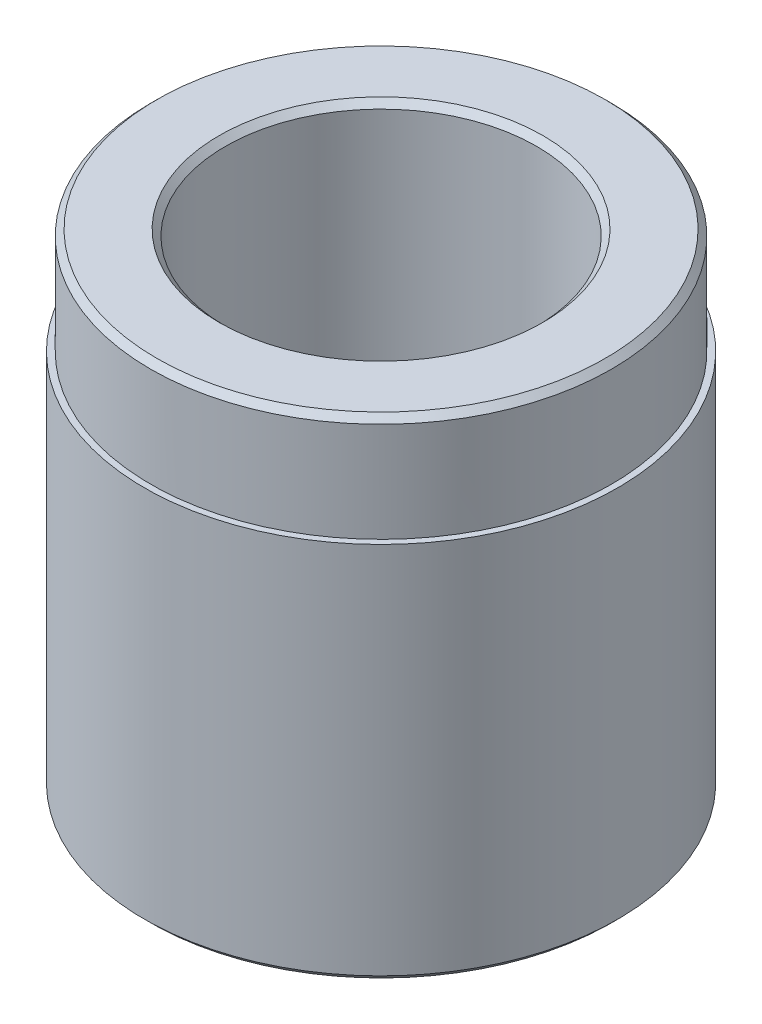
SolidWorks part; units mm, degrees
material "20"
ref_plane "前视基准面" through (0, 0, 0) normal (0, 0, 1) x (1, 0, 0)
ref_plane "上视基准面" through (0, 0, 0) normal (0, 1, 0) x (1, 0, 0)
ref_plane "右视基准面" through (0, 0, 0) normal (1, 0, 0) x (0, 0, -1)
sketch "草图1" plane through (0, 0, 0) normal (0, 0, 1) x (1, 0, 0)
  line L0 (0, 0) -> (0, 76.6338) construction
  line L1 (0, 0) -> (25, 0) construction
  line L2 (25, 0) -> (25, 78)
  line L3 (25, 78) -> (37, 78)
  line L4 (37, 78) -> (37, 61)
  line L5 (37, 61) -> (38, 61)
  line L6 (38, 61) -> (38, 0)
  line L7 (38, 0) -> (25, 0)
  dimension "D1" = 76
  dimension "D2" = 50
  dimension "D3" = 78
  dimension "D4" = 61
  dimension "D5" = 74
revolve "旋转1" add sketch "草图1" angle 360 about L0
chamfer "倒角1" distance 1 angle 45 4 edges at (0, 0, -38) (0, 0, -25) (0, 78, -25) (0, 78, -37)
